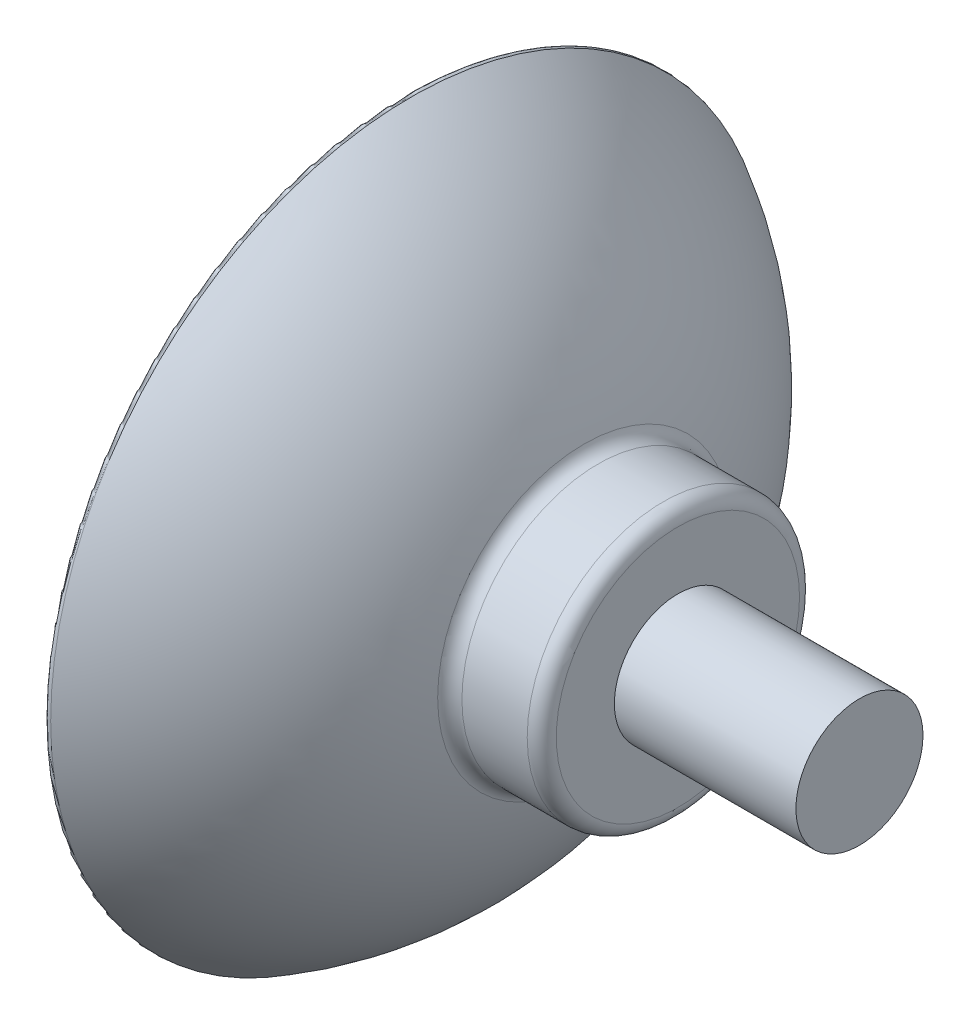
SolidWorks part; units mm, degrees
ref_plane "Front Plane" through (0, 0, 0) normal (0, 0, 1) x (1, 0, 0)
ref_plane "Top Plane" through (0, 0, 0) normal (0, 1, 0) x (1, 0, 0)
ref_plane "Right Plane" through (0, 0, 0) normal (1, 0, 0) x (0, 0, -1)
sketch "Sketch1" plane through (0, 0, 0) normal (0, 0, 1) x (1, 0, 0)
  line L0 (0, 0) -> (0, 4002.8347) construction
  line L1 (0, 0) -> (-4002.8347, 0) construction
  line L2 (-10, 20) -> (-10, -8.3558) construction
  line L3 (0, 0) -> (5, 0)
  line L4 (0, 0) -> (0, 7.5)
  line L5 (0, 7.5) -> (5, 7.5)
  line L6 (5, 0) -> (5, 7.5)
  line L7 (2, 0) -> (4, 0)
  line L8 (2, 0) -> (2, 4.75)
  line L9 (2, 4.75) -> (4, 4.75)
  line L10 (4, 0) -> (4, 4.75)
  line L11 (-24.2646, 20) -> (5.492, 20) construction
  line L12 (-10, 20) -> (-10, 19.5)
  arc A0 (0, 7.5) -> (-10, 20) centre (-19.3122, 2.3002) ccw
  arc A1 (0, 1.0609) -> (-10, 19.5) centre (-22, 1.0609) ccw
  dimension "D9" = 22
  dimension "D10" = 20
  dimension "D1" = 7.5
  dimension "D2" = 5
  dimension "D3" = 4.75
  dimension "D4" = 2
  dimension "D5" = 1
  dimension "D6" = 10
  dimension "D7" = 20
  dimension "D8" = 0.5
revolve "Revolve2" add sketch "Sketch1" angle 360 about L1
sketch "Sketch2" plane through (5, 0, 0) normal (1, 0, 0) x (0, 0, -1)
  circle A0 centre (0, 0) radius 2.4
  dimension "D1" = 4.8
extrude "Cut-Extrude1" cut sketch "Sketch2" against normal blind 1
fillet "Fillet2" radius 0.8 3 edges at (5, 0, -2.4) (5, 0, -7.5) (0, 0, -7.5)
fillet "Fillet3" radius 0.2 2 edges at (-10, 0, -19.5) (-10, 0, -20)
sketch "Sketch6" plane through (5, 0, 0) normal (1, 0, 0) x (0, 0, -1)
  circle A0 centre (0, 0) radius 2.4
sketch "Sketch7" plane through (5, 0, 0) normal (1, 0, 0) x (0, 0, -1)
  circle A0 centre (0, 0) radius 3.5
  dimension "D1" = 7
extrude "Boss-Extrude1" add sketch "Sketch7" along normal blind 10
